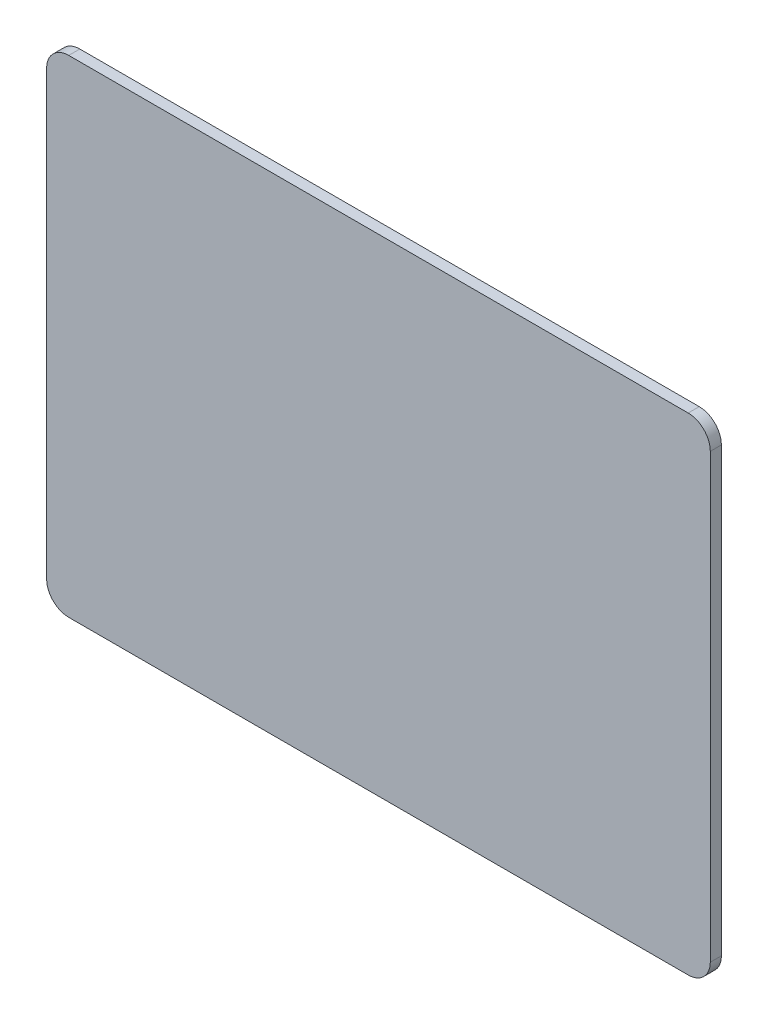
SolidWorks part; units mm, degrees
ref_plane "Front Plane" through (0, 0, 0) normal (0, 0, 1) x (1, 0, 0)
ref_plane "Top Plane" through (0, 0, 0) normal (0, 1, 0) x (1, 0, 0)
ref_plane "Right Plane" through (0, 0, 0) normal (1, 0, 0) x (0, 0, -1)
sketch "Sketch1" plane through (0, 0, 0) normal (0, 0, 1) x (1, 0, 0)
  line L1 (-290, 110) -> (-10, 110)
  line L2 (-300, 100) -> (-300, -100)
  line L3 (-290, -110) -> (-10, -110)
  line L4 (0, 100) -> (0, -100)
  arc A0 (-290, 110) -> (-300, 100) centre (-290, 100) ccw
  arc A1 (-10, 110) -> (0, 100) centre (-10, 100) cw
  arc A2 (-10, -110) -> (0, -100) centre (-10, -100) ccw
  arc A3 (-300, -100) -> (-290, -110) centre (-290, -100) ccw
  point P4 (0, 0)
  point P5 (0, 0)
  point P9 (-300, 110)
  point P12 (0, 110)
  dimension "D3" = 10
  dimension "D4" = 10
  dimension "D1" = 220
  dimension "D2" = 300
extrude "Boss-Extrude1" add sketch "Sketch1" along normal blind 5
